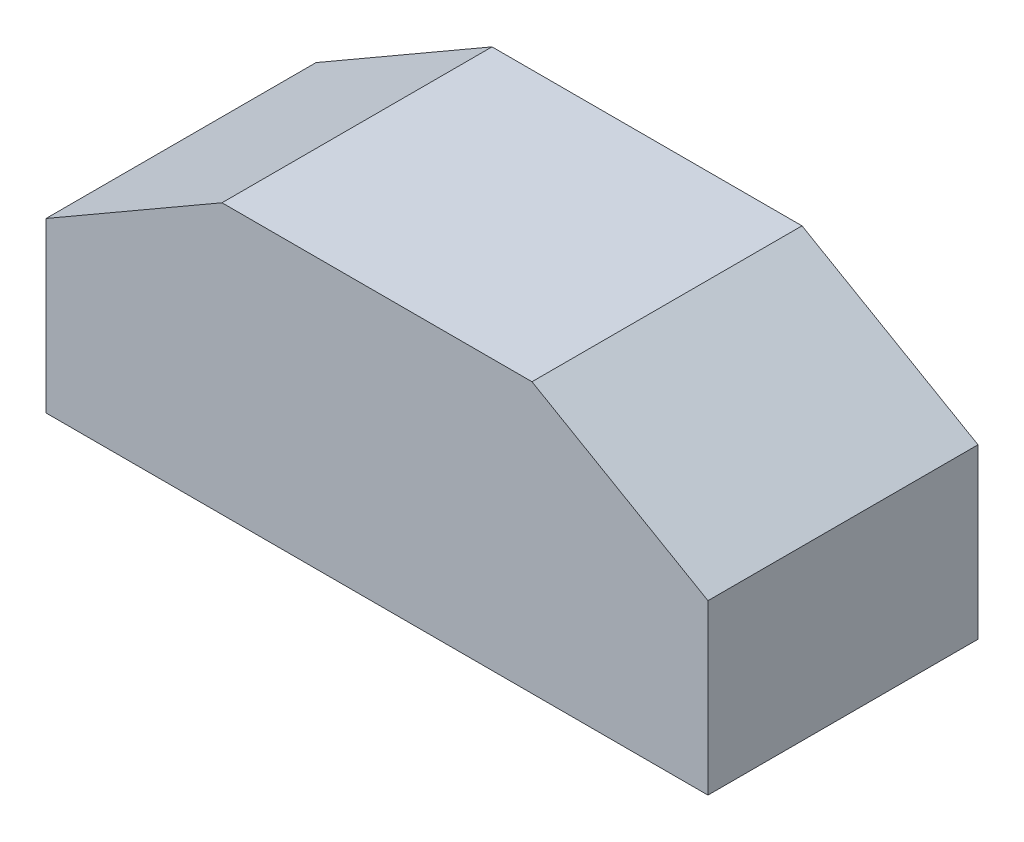
SolidWorks part; units mm, degrees
ref_plane "Front Plane" through (0, 0, 0) normal (0, 0, 1) x (1, 0, 0)
ref_plane "Top Plane" through (0, 0, 0) normal (0, 1, 0) x (1, 0, 0)
ref_plane "Right Plane" through (0, 0, 0) normal (1, 0, 0) x (0, 0, -1)
sketch "Sketch1" plane through (0, 0, 0) normal (0, 0, 1) x (1, 0, 0)
  line L0 (0, 0) -> (15, 0)
  line L1 (0, 0) -> (-8.6603, -5)
  line L2 (15, 0) -> (23.6603, -5)
  line L3 (-0.5359, 2) -> (-9.6603, -3.2679)
  line L4 (-0.5359, 2) -> (15.5359, 2)
  line L5 (15.5359, 2) -> (24.6603, -3.2679)
  line L6 (-8.6603, -5) -> (-9.6603, -3.2679)
  line L7 (-9.6603, -3.2679) -> (-9.6464, -3.1381)
  line L8 (23.6603, -5) -> (24.6603, -3.2679)
  dimension "D1" = 15
  dimension "D2" = 10
  dimension "D3" = 10
  dimension "D4" = 150
  dimension "D5" = 2
extrude "Boss-Extrude1" add sketch "Sketch1" along normal blind 10 contours L2 L8 L5 L4 L3 L6 L1 L0
sketch "Sketch2" plane through (0, 0, 10) normal (0, 0, 1) x (1, 0, 0)
  line L0 (-8.6603, -5) -> (23.6603, -5)
  line L1 (23.6603, -5) -> (24.6603, -3.2679)
  line L2 (24.6603, -3.2679) -> (15.5359, 2)
  line L3 (15.5359, 2) -> (-0.5359, 2)
  line L4 (-0.5359, 2) -> (-9.6603, -3.2679)
  line L5 (-9.6603, -3.2679) -> (-8.6603, -5)
  line L6 (23.6603, -5) -> (23.7384, -5.1219)
  line L7 (-8.6603, -5) -> (-8.6603, -12.1219)
  line L8 (-8.6603, -12.1219) -> (23.7384, -12.1219)
  line L9 (23.7384, -12.1219) -> (23.7384, -5.1219)
  point P15 (0, 0)
  line M1 (15, 0) -> (23.6603, -5)
  line M3 (24.6603, -3.2679) -> (15.5359, 2)
  line M4 (15.5359, 2) -> (-0.5359, 2)
  line M5 (-0.5359, 2) -> (-9.6603, -3.2679)
  line M6 (-9.6603, -3.2679) -> (-8.6603, -5)
  line M7 (-8.6603, -5) -> (0, 0)
  line M8 (0, 0) -> (15, 0)
  dimension "D1" = 7
extrude "Boss-Extrude2" add sketch "Sketch2" along normal blind 2 contours L0 M7 M1 M8 | L1 M1 M3 M4 M5 M6 M7 M8
sketch "Sketch3" plane through (0, 0, 0) normal (0, 0, -1) x (-1, 0, 0)
  line L0 (-24.6603, -3.2679) -> (-15.5359, 2)
  line L1 (-15.5359, 2) -> (0.5359, 2)
  line L2 (0.5359, 2) -> (9.6603, -3.2679)
  line L3 (9.6603, -3.2679) -> (8.6603, -5)
  line L4 (8.6603, -5) -> (-23.6603, -5)
  line L5 (-23.6603, -5) -> (-24.6603, -3.2679)
extrude "Boss-Extrude3" add sketch "Sketch3" along normal blind 2
sketch "Sketch4" plane through (0, 0, 12) normal (0, 0, 1) x (1, 0, 0)
  line L0 (-8.6603, -5) -> (-8.6603, -12)
  line L1 (-8.6603, -12) -> (23.6603, -12)
  line L2 (23.6603, -5) -> (23.6603, -12)
  line L10 (-8.6603, -5) -> (23.6603, -5)
  line L11 (23.6603, -5) -> (24.6603, -3.2679)
  line L12 (24.6603, -3.2679) -> (15.5359, 2)
  line L13 (15.5359, 2) -> (-0.5359, 2)
  line L14 (-0.5359, 2) -> (-9.6603, -3.2679)
  line L15 (-9.6603, -3.2679) -> (-8.6603, -5)
  line L16 (-8.6603, -5) -> (23.6603, -5)
  dimension "D1" = 7
  dimension "D2" = 0
extrude "Boss-Extrude4" add sketch "Sketch4" against normal blind 2
sketch "Sketch5" plane through (0, 0, -2) normal (0, 0, -1) x (-1, 0, 0)
  line L0 (-23.6603, -5) -> (8.6603, -5)
  line L1 (8.6603, -5) -> (8.6603, -12)
  line L2 (8.6603, -12) -> (-23.6603, -12)
  line L3 (-23.6603, -12) -> (-23.6603, -5)
extrude "Boss-Extrude5" add sketch "Sketch5" against normal blind 2
sketch "Sketch8" plane through (0, 0, 12) normal (0, 0, 1) x (1, 0, 0)
  line L0 (-9.6603, -3.2679) -> (-9.6603, -12)
  line L1 (-9.6603, -12) -> (-8.6603, -12)
  line L2 (-8.6603, -12) -> (-8.6603, -5)
  line L3 (-8.6603, -5) -> (-9.6603, -3.2679)
extrude "Boss-Extrude9" add sketch "Sketch8" against normal blind 14
sketch "Sketch9" plane through (0, 0, -2) normal (0, 0, -1) x (-1, 0, 0)
  line L0 (-24.6603, -3.2679) -> (-23.6603, -5)
  line L1 (-23.6603, -5) -> (-23.6603, -12)
  line L2 (-24.6603, -3.2679) -> (-24.6603, -12)
  line L3 (-24.6603, -12) -> (-23.6603, -12)
  line L4 (-23.6603, -12) -> (-23.6137, -12.0498)
extrude "Boss-Extrude10" add sketch "Sketch9" against normal blind 14 contours L1 L0 L2 L3
